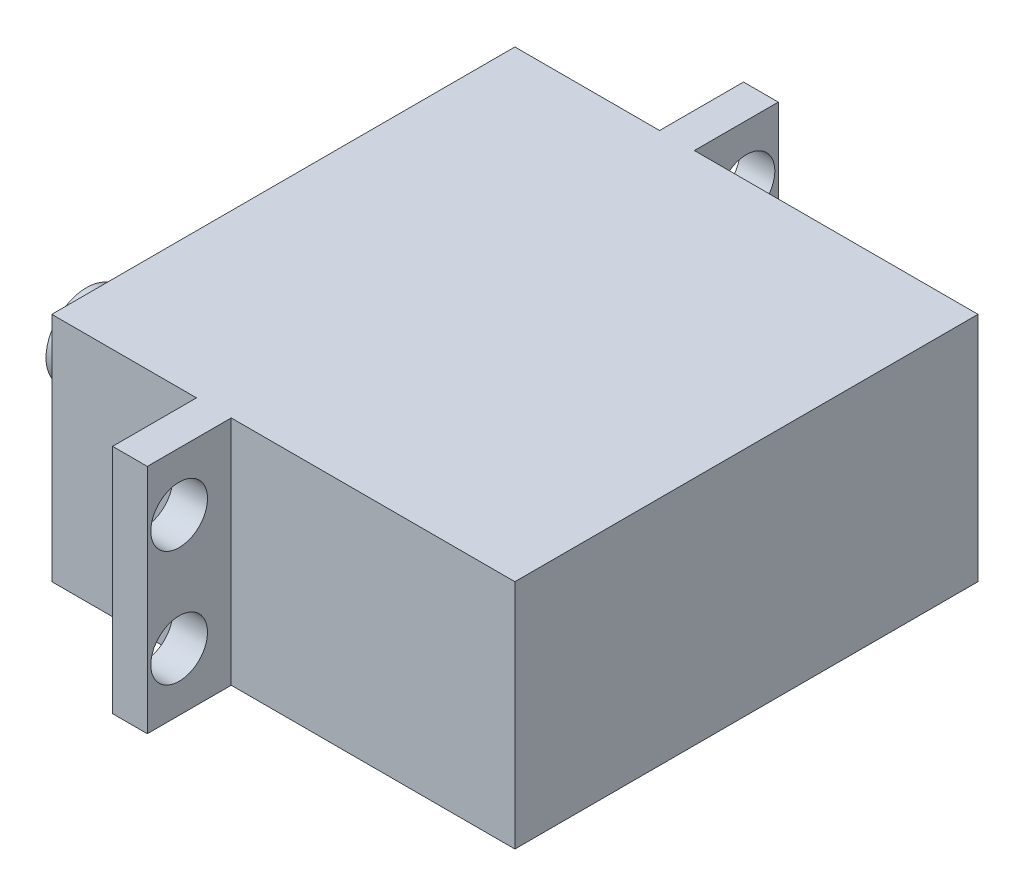
SolidWorks part; units mm, degrees
ref_plane "前视基准面" through (0, 0, 0) normal (0, 0, 1) x (1, 0, 0)
ref_plane "上视基准面" through (0, 0, 0) normal (0, 1, 0) x (1, 0, 0)
ref_plane "右视基准面" through (0, 0, 0) normal (1, 0, 0) x (0, 0, -1)
sketch "草图1" plane through (0, 0, 0) normal (0, 1, 0) x (1, 0, 0)
  line L1 (-20, 20) -> (20, 20)
  line L2 (-20, 20) -> (-20, -20)
  line L3 (-20, -20) -> (20, -20)
  line L4 (20, 20) -> (20, -20)
  line L5 (-20, 20) -> (20, -20) construction
  line L6 (-20, -20) -> (20, 20) construction
  point P0 (0, 0)
  dimension "D1" = 40
  dimension "D2" = 40
extrude "凸台-拉伸1" add sketch "草图1" along normal blind 20
ref_plane "基准面1" through (0, 0, -20) normal (0, 0, -1) x (-1, 0, 0)
sketch "草图4" plane through (0, 0, -20) normal (0, 0, -1) x (-1, 0, 0)
  line L0 (-20, 10) -> (4.5, 10) construction
  line L1 (-20, 20) -> (-20, 0) construction
  line L2 (-20, 20) -> (20, 20) construction
  line L3 (4.5, 20) -> (7.5, 20)
  line L4 (4.5, 20) -> (4.5, 0)
  line L5 (4.5, 0) -> (7.5, 0)
  line L6 (7.5, 20) -> (7.5, 0)
  line L7 (-20, 0) -> (20, 0) construction
  dimension "D1" = 24.5
  dimension "D2" = 3
extrude "凸台-拉伸2" add sketch "草图4" along normal blind 7.25 and the other way blind 47.25
ref_plane "基准面2" through (-7.5, 0, 0) normal (-1, 0, 0) x (0, 0, 1)
sketch "草图5" plane through (-7.5, 0, 0) normal (-1, 0, 0) x (0, 0, 1)
  line L0 (-27.25, 10) -> (-27.25, 15) construction
  line L1 (-27.25, 0) -> (-27.25, 20) construction
  line L2 (-27.25, 15) -> (-24.5, 15) construction
  line L3 (0, 20) -> (0, 0) construction
  line L4 (-20, 20) -> (20, 20) construction
  line L5 (-27.25, 10) -> (27.25, 10) construction
  line L6 (27.25, 0) -> (27.25, 20) construction
  circle A0 centre (-24.5, 15) radius 2.45
  circle A1 centre (24.5, 15) radius 2.45
  circle A2 centre (24.5, 5) radius 2.45
  circle A3 centre (-24.5, 5) radius 2.45
  dimension "D3" = 4.9
  dimension "D1" = 5
  dimension "D2" = 49
extrude "切除-拉伸3" cut sketch "草图5" against normal blind 7.25
ref_plane "基准面3" through (-20, 0, 0) normal (-1, 0, 0) x (0, 0, 1)
sketch "草图6" plane through (-20, 0, 0) normal (-1, 0, 0) x (0, 0, 1)
  line L0 (-20, 10) -> (10, 10) construction
  line L1 (-20, 11) -> (-20, -11) construction
  circle A0 centre (10, 10) radius 3.5
  dimension "D2" = 7
  dimension "D1" = 30
extrude "凸台-拉伸3" add sketch "草图6" along normal blind 7
ref_plane "基准面4" through (-27, 0, 0) normal (-1, 0, 0) x (0, 0, 1)
sketch "草图7" plane through (-20, 0, 0) normal (-1, 0, 0) x (0, 0, 1)
  circle A0 centre (10, 10) radius 5
  dimension "D1" = 10
extrude "凸台-拉伸4" add sketch "草图7" along normal blind 2.5
sketch "草图8" plane through (-27, 0, 0) normal (-1, 0, 0) x (0, 0, 1)
  line L0 (10, 6.5) -> (10, 13.5) construction
  circle A0 centre (10, 10) radius 3.5 construction
  circle A1 centre (10, 10) radius 3.5 construction
